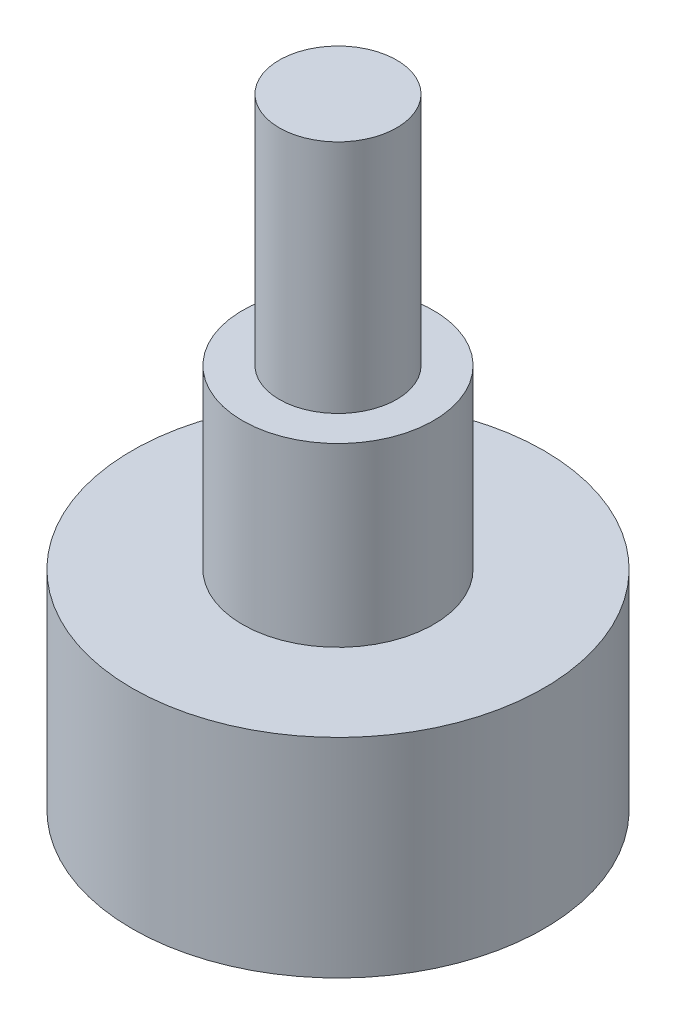
SolidWorks part; units mm, degrees
ref_plane "Front Plane" through (0, 0, 0) normal (0, 0, 1) x (1, 0, 0)
ref_plane "Top Plane" through (0, 0, 0) normal (0, 1, 0) x (1, 0, 0)
ref_plane "Right Plane" through (0, 0, 0) normal (1, 0, 0) x (0, 0, -1)
sketch "Sketch1" plane through (0, 0, 0) normal (0, 1, 0) x (1, 0, 0)
  circle A0 centre (0, 0) radius 11.115
  dimension "D1" = 22.23
extrude "Boss-Extrude1" add sketch "Sketch1" along normal blind 11.25
sketch "Sketch2" plane through (0, 11.25, 0) normal (0, 1, 0) x (1, 0, 0)
  circle A0 centre (0, 0) radius 5.1585
  dimension "D1" = 10.317
extrude "Boss-Extrude2" add sketch "Sketch2" along normal blind 9.53
sketch "Sketch3" plane through (0, 11.25, 0) normal (0, 1, 0) x (1, 0, 0)
  circle A0 centre (0, 0) radius 3.171
  dimension "D1" = 6.342
extrude "Boss-Extrude3" add sketch "Sketch3" along normal blind 22.23
